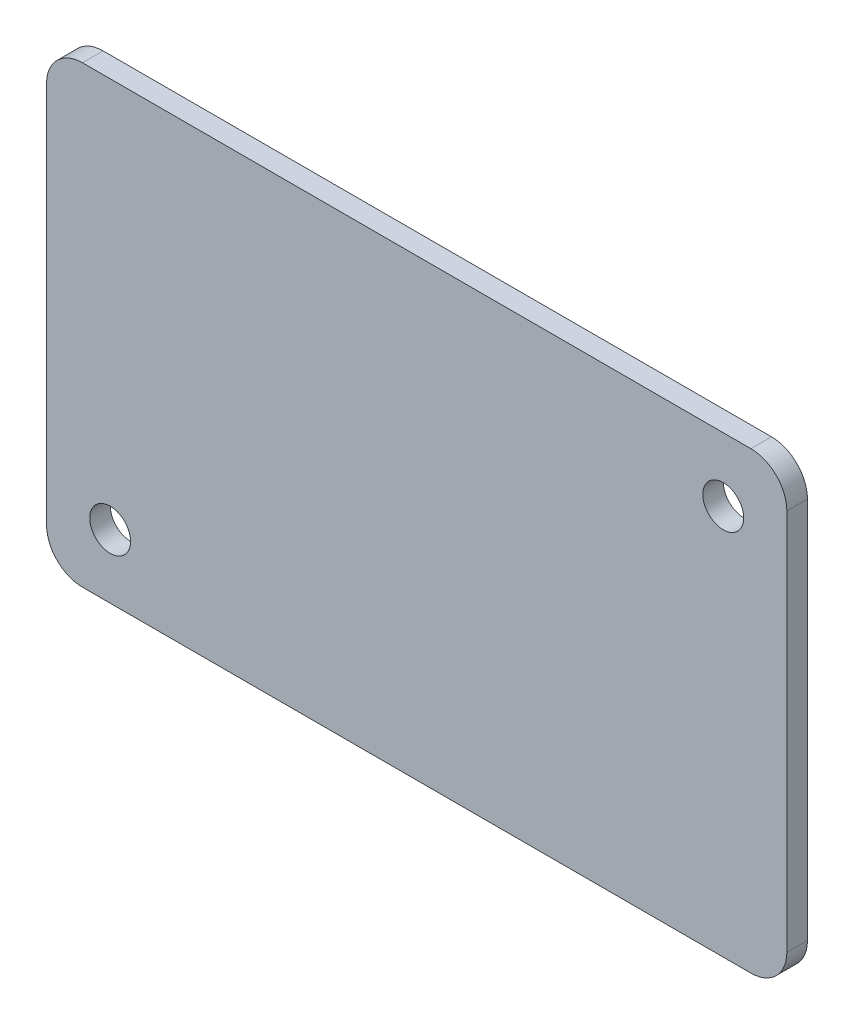
SolidWorks part; units mm, degrees
ref_plane "Front Plane" through (0, 0, 0) normal (0, 0, 1) x (1, 0, 0)
ref_plane "Top Plane" through (0, 0, 0) normal (0, 1, 0) x (1, 0, 0)
ref_plane "Right Plane" through (0, 0, 0) normal (1, 0, 0) x (0, 0, -1)
sketch "Sketch1" plane through (0, 0, 0) normal (0, 0, 1) x (1, 0, 0)
  line L0 (-28.7528, 0) -> (28.7528, 0) construction
  line L1 (28.7528, 17.6403) -> (-28.7528, 17.6403)
  line L2 (28.7528, 17.6403) -> (28.7528, -17.6403)
  line L3 (28.7528, -17.6403) -> (-28.7528, -17.6403)
  line L4 (-28.7528, 17.6403) -> (-28.7528, -17.6403)
  line L5 (28.7528, 17.6403) -> (-28.7528, -17.6403) construction
  line L6 (28.7528, -17.6403) -> (-28.7528, 17.6403) construction
  line L7 (0, 17.6403) -> (0, -17.6403) construction
  circle A0 centre (-23.8125, -12.7) radius 1.5875
  circle A1 centre (23.8125, 12.7) radius 1.5875
  point P0 (0, 0)
  dimension "D7" = 3.175
  dimension "D1" = 57.5056
  dimension "D2" = 35.2806
  dimension "D3" = 25.4
  dimension "D4" = 12.7
  dimension "D5" = 47.625
  dimension "D6" = 23.8125
extrude "Boss-Extrude1" add sketch "Sketch1" along normal blind 1.6002
fillet "Fillet1" radius 2.794 4 edges at (-28.7528, 17.6403, 0.8001) (-28.7528, -17.6403, 0.8001) (28.7528, -17.6403, 0.8001) (28.7528, 17.6403, 0.8001)
